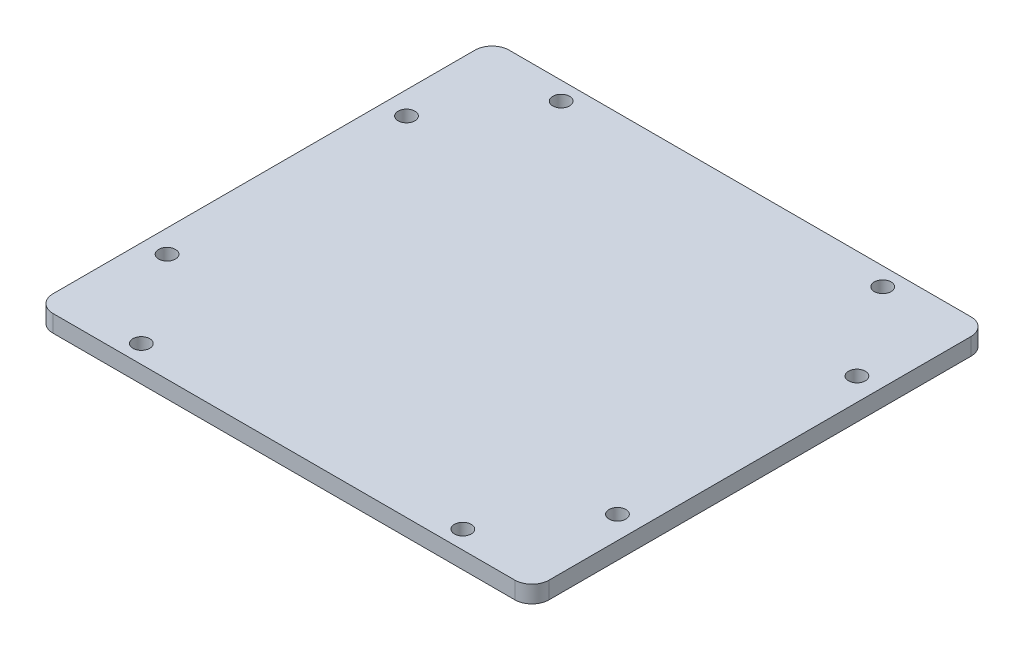
SolidWorks part; units mm, degrees
ref_plane "Front Plane" through (0, 0, 0) normal (0, 0, 1) x (1, 0, 0)
ref_plane "Top Plane" through (0, 0, 0) normal (0, 1, 0) x (1, 0, 0)
ref_plane "Right Plane" through (0, 0, 0) normal (1, 0, 0) x (0, 0, -1)
sketch "Sketch1" plane through (0, 0, 0) normal (0, 1, 0) x (1, 0, 0)
  line L0 (0, -40) -> (0, 40) construction
  line L1 (-40.5, 40) -> (40.5, 40)
  line L2 (-43.5, 37) -> (-43.5, -37)
  line L3 (-40.5, -40) -> (40.5, -40)
  line L4 (43.5, 37) -> (43.5, -37)
  line L5 (-43.5, 40) -> (43.5, -40) construction
  line L6 (-43.5, -40) -> (43.5, 40) construction
  line L7 (43.5, 0) -> (-43.5, 0) construction
  circle A0 centre (28.198, -36.819) radius 1.475
  circle A1 centre (28.198, 36.819) radius 1.475
  circle A2 centre (-28.198, 36.819) radius 1.475
  circle A3 centre (-28.198, -36.819) radius 1.475
  circle A4 centre (39.5, 21) radius 1.475
  circle A5 centre (-39.5, 21) radius 1.475
  circle A6 centre (39.5, -21) radius 1.475
  circle A7 centre (-39.5, -21) radius 1.475
  arc A9 (43.5, -37) -> (40.5, -40) centre (40.5, -37) cw
  arc A10 (-40.5, -40) -> (-43.5, -37) centre (-40.5, -37) cw
  arc A11 (-40.5, 40) -> (-43.5, 37) centre (-40.5, 37) ccw
  arc A12 (43.5, 37) -> (40.5, 40) centre (40.5, 37) ccw
  point P0 (0, 0)
  dimension "D5" = 2.95
  dimension "D8" = 2.95
  dimension "D9" = 3
  dimension "D1" = 87
  dimension "D2" = 80
  dimension "D3" = 36.819
  dimension "D4" = 28.198
  dimension "D6" = 21
  dimension "D7" = 39.5
extrude "Boss-Extrude1" add sketch "Sketch1" along normal blind 3
